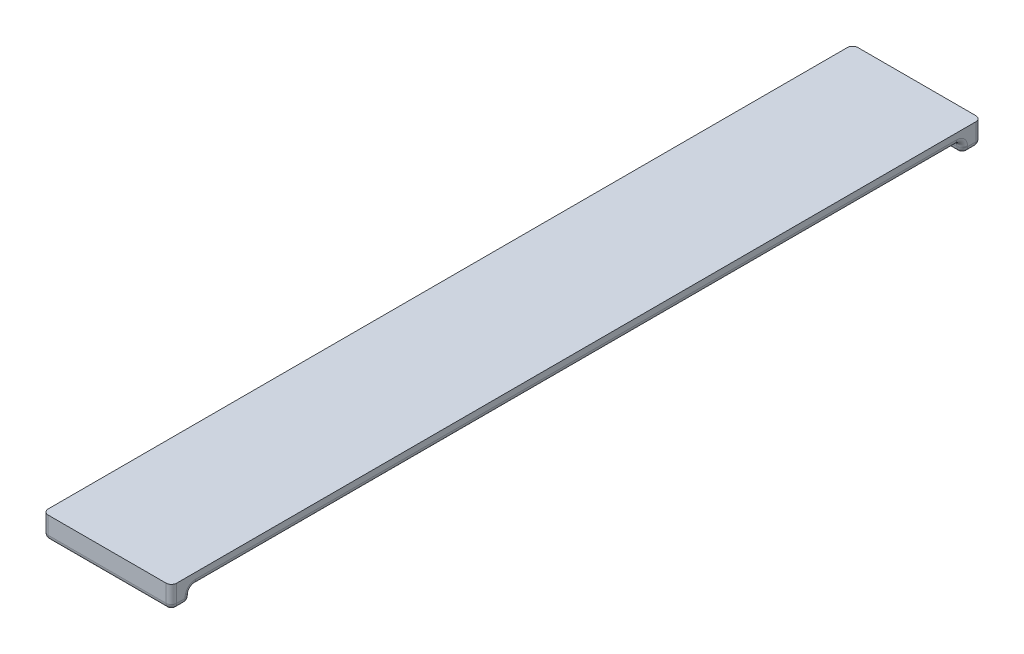
SolidWorks part; units mm, degrees
ref_plane "Front Plane" through (0, 0, 0) normal (0, 0, 1) x (1, 0, 0)
ref_plane "Top Plane" through (0, 0, 0) normal (0, 1, 0) x (1, 0, 0)
ref_plane "Right Plane" through (0, 0, 0) normal (1, 0, 0) x (0, 0, -1)
sketch "Sketch1" plane through (0, 0, 0) normal (0, 1, 0) x (1, 0, 0)
  line L0 (-17.6031, -25.4) -> (-9.1435, -25.4) construction
  line L1 (-17.6031, -25.4) -> (-17.6031, 25.4)
  line L2 (-17.6031, 25.4) -> (-9.1435, 25.4) construction
  line L3 (-9.1435, -25.4) -> (-9.1435, 25.4)
  line L4 (-17.6031, -25.4) -> (-9.1435, 25.4) construction
  line L5 (-17.6031, 25.4) -> (-9.1435, -25.4) construction
  line L6 (-1.375, 0) -> (1.375, 0) construction
  line L7 (-17.6031, -25.4) -> (-9.1435, -25.4) construction
  line L8 (-17.6031, -25.4) -> (-17.6031, -26.65)
  line L9 (-17.6031, -26.65) -> (-9.1435, -26.65)
  line L10 (-9.1435, -25.4) -> (-9.1435, -26.65)
  line L11 (-17.6031, -25.4) -> (-9.1435, -26.65) construction
  line L12 (-17.6031, -26.65) -> (-9.1435, -25.4) construction
  line L13 (-17.6031, 25.4) -> (-9.1435, 26.65) construction
  line L14 (-17.6031, 26.65) -> (-9.1435, 25.4) construction
  line L15 (-9.1435, 25.4) -> (-9.1435, 26.65)
  line L16 (-17.6031, 26.65) -> (-9.1435, 26.65)
  line L17 (-17.6031, 25.4) -> (-17.6031, 26.65)
  point P4 (-13.3733, 0)
  point P7 (-13.3733, -26.025)
  dimension "D1" = 8.4596
  dimension "D2" = 50.8
  dimension "D3" = 1.25
extrude "Boss-Extrude1" add sketch "Sketch1" along normal blind 0.75
sketch "Sketch2" plane through (0, 0, 0) normal (0, -1, 0) x (1, 0, 0)
  line L0 (-17.6031, -25.4) -> (-9.1435, -26.65) construction
  line L1 (-17.6031, 25.4) -> (-9.1435, 25.4)
  line L2 (-17.6031, 25.4) -> (-17.6031, 26.65)
  line L3 (-17.6031, 26.65) -> (-9.1435, 26.65)
  line L4 (-9.1435, 25.4) -> (-9.1435, 26.65)
  line L5 (-17.6031, 25.4) -> (-9.1435, 26.65) construction
  line L6 (-17.6031, 26.65) -> (-9.1435, 25.4) construction
  line L7 (-17.6031, -25.4) -> (-9.1435, -25.4)
  line L8 (-17.6031, -25.4) -> (-17.6031, -26.65)
  line L9 (-17.6031, -26.65) -> (-9.1435, -26.65)
  line L10 (-9.1435, -25.4) -> (-9.1435, -26.65)
  line L11 (-17.6031, -25.4) -> (-9.1435, -26.65) construction
  line L12 (-17.6031, -26.65) -> (-9.1435, -25.4) construction
  point P0 (-13.3733, 26.025)
  point P7 (-13.3733, -26.025)
extrude "Boss-Extrude2" add sketch "Sketch2" along normal blind 0.75
sketch "Sketch3" plane through (0, 0, 0) normal (0, -1, 0) x (1, 0, 0)
  line L0 (-17.6031, 25.4) -> (-17.6031, -25.4) construction
  line L1 (-17.6031, -24.3) -> (-12.1031, -24.3)
  line L2 (-17.6031, -24.3) -> (-17.6031, -21.3)
  line L3 (-17.6031, -21.3) -> (-12.1031, -21.3)
  line L4 (-12.1031, -24.3) -> (-12.1031, -21.3) construction
  line L5 (-17.6031, -24.3) -> (-12.1031, -21.3) construction
  line L6 (-17.6031, -21.3) -> (-12.1031, -24.3) construction
  line L7 (-17.6031, -25.4) -> (-9.1435, -25.4) construction
  arc A0 (-12.1031, -24.3) -> (-12.1031, -21.3) centre (-12.1031, -22.8) ccw
  point P4 (-14.8531, -22.8)
  dimension "D1" = 1.1
  dimension "D2" = 3
  dimension "D3" = 5.5
extrude "Boss-Extrude3" add sketch "Sketch3" along normal blind 1.25
pattern_linear "LPattern1" count 10 spacing 5.068 along (0, 0, 1) of "Boss-Extrude3"
fillet "Fillet1" radius 0.35 120 edges at (-17.6031, -0.625, 24.312) (-17.6031, -0.375, 25.4) (-9.1435, -0.375, 25.4) (-9.1435, -0.375, -25.4) (-17.6031, -0.375, -25.4) (-17.6031, -0.625, -24.3) (-17.6031, -0.625, -21.3) (-17.6031, -0.625, -19.232) (-17.6031, -0.625, -16.232) (-17.6031, -0.625, -14.164) (-17.6031, -0.625, -11.164) (-17.6031, -0.625, -9.096) (-17.6031, -0.625, -6.096) (-17.6031, -0.625, -4.028) (-17.6031, -0.625, -1.028) (-17.6031, -0.625, 1.04) (-17.6031, -0.625, 4.04) (-17.6031, -0.625, 6.108) (-17.6031, -0.625, 9.108) (-17.6031, -0.625, 11.176) (-17.6031, -0.625, 14.176) (-17.6031, -0.625, 16.244) (-17.6031, -0.625, 19.244) (-17.6031, -0.625, 21.312) (-14.8531, -1.25, -24.3) (-14.8531, -1.25, -21.3) (-13.3733, -0.75, 25.4) (-17.6031, -0.75, 26.025) (-13.3733, -0.75, 26.65) (-9.1435, -0.75, 26.025) (-14.8531, -1.25, -16.232) (-10.6031, -1.25, -17.732) (-14.8531, -1.25, -19.232) (-17.6031, -1.25, -17.732) (-10.6031, 0, 22.812) (-14.8531, 0, 24.312) (-17.6031, 0, 24.856) (-13.3733, 0, 25.4) (-9.1435, 0, 0) (-13.3733, 0, -25.4) (-17.6031, 0, -24.85) (-14.8531, 0, -24.3) (-10.6031, 0, -22.8) (-14.8531, 0, -21.3) (-17.6031, 0, -20.266) (-14.8531, 0, -19.232) (-10.6031, 0, -17.732) (-14.8531, 0, -16.232) (-17.6031, 0, -15.198) (-14.8531, 0, -14.164) (-10.6031, 0, -12.664) (-14.8531, 0, -11.164) (-17.6031, 0, -10.13) (-14.8531, 0, -9.096) (-10.6031, 0, -7.596) (-14.8531, 0, -6.096) (-17.6031, 0, -5.062) (-14.8531, 0, -4.028) (-10.6031, 0, -2.528) (-14.8531, 0, -1.028) (-17.6031, 0, 0.006) (-14.8531, 0, 1.04) (-10.6031, 0, 2.54) (-14.8531, 0, 4.04) (-17.6031, 0, 5.074) (-14.8531, 0, 6.108) (-10.6031, 0, 7.608) (-14.8531, 0, 9.108) (-17.6031, 0, 10.142) (-14.8531, 0, 11.176) (-10.6031, 0, 12.676) (-14.8531, 0, 14.176) (-17.6031, 0, 15.21) (-14.8531, 0, 16.244) (-10.6031, 0, 17.744) (-14.8531, 0, 19.244) (-17.6031, 0, 20.278) (-14.8531, 0, 21.312) (-14.8531, -1.25, 19.244) (-10.6031, -1.25, 17.744) (-14.8531, -1.25, 16.244) (-17.6031, -1.25, 17.744) (-14.8531, -1.25, 24.312) (-10.6031, -1.25, 22.812) (-14.8531, -1.25, 21.312) (-17.6031, -1.25, 22.812) (-13.3733, -0.75, -26.65) (-17.6031, -0.75, -26.025) (-13.3733, -0.75, -25.4) (-9.1435, -0.75, -26.025) (-14.8531, -1.25, -11.164) (-10.6031, -1.25, -12.664) (-14.8531, -1.25, -14.164) (-17.6031, -1.25, -12.664) (-14.8531, -1.25, -6.096) (-10.6031, -1.25, -7.596) (-14.8531, -1.25, -9.096) (-17.6031, -1.25, -7.596) (-14.8531, -1.25, -1.028) (-10.6031, -1.25, -2.528) (-14.8531, -1.25, -4.028) (-17.6031, -1.25, -2.528) (-14.8531, -1.25, 4.04) (-10.6031, -1.25, 2.54) (-14.8531, -1.25, 1.04) (-17.6031, -1.25, 2.54) (-14.8531, -1.25, 9.108) (-10.6031, -1.25, 7.608) (-14.8531, -1.25, 6.108) (-17.6031, -1.25, 7.608) (-14.8531, -1.25, 14.176) (-10.6031, -1.25, 12.676) (-14.8531, -1.25, 11.176) (-17.6031, -1.25, 12.676) (-17.6031, 0, -26.65) (-9.1435, 0, -26.65) (-17.6031, 0, 26.65) (-9.1435, 0, 26.65) (-17.6031, -1.25, -22.8) (-10.6031, -1.25, -22.8)
